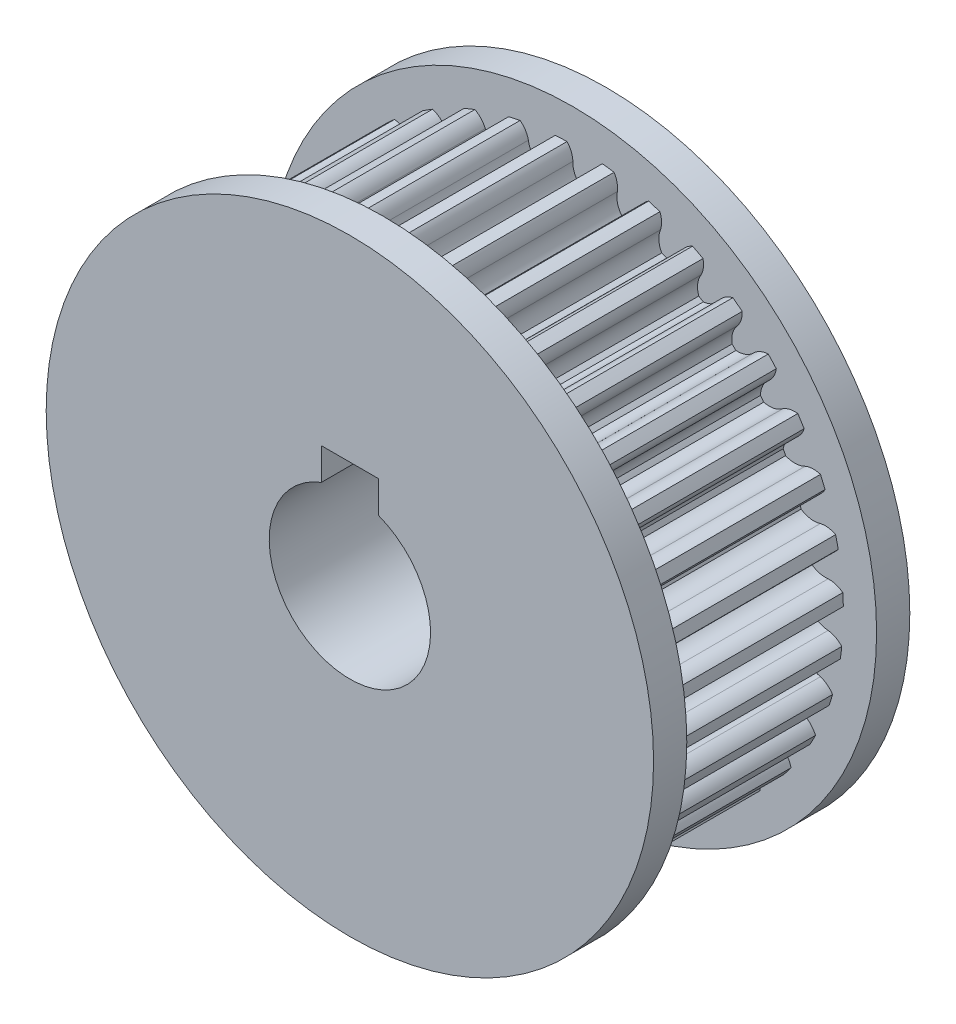
SolidWorks part; units mm, degrees
ref_plane "Alzado" through (0, 0, 0) normal (0, 0, 1) x (1, 0, 0)
ref_plane "Planta" through (0, 0, 0) normal (0, 1, 0) x (1, 0, 0)
ref_plane "Vista lateral" through (0, 0, 0) normal (1, 0, 0) x (0, 0, -1)
sketch "Croquis2" plane through (0, 0, 0) normal (0, 0, 1) x (1, 0, 0)
  circle A0 centre (0, 0) radius 25.125 construction
  arc A1 (3.1031, 28.3306) -> (-0.6204, 28.4932) centre (0, 0) ccw construction
  arc A2 (2.3548, 26.8971) -> (0, 27) centre (0, 0) ccw construction
  arc A3 (0, 27) -> (-0.6204, 28.4932) centre (-2.3548, 26.8971) ccw construction
  arc A5 (0, 27) -> (0.816, 25.1117) centre (2.3548, 26.8971) ccw construction
  circle A7 centre (0, 0) radius 28.5
  arc A8 (3.1031, 28.3306) -> (2.3548, 26.8971) centre (4.6916, 26.5893) ccw construction
  arc A10 (1.3772, 25.0872) -> (2.3548, 26.8971) centre (0, 27) ccw construction
  dimension "D1" = 50.25
  dimension "D2" = 57
  dimension "D3" = 54
  dimension "D4" = 4.714
extrude "Saliente-Extruir2" add sketch "Croquis2" along normal blind 20
sketch "Croquis5" plane through (0, 0, 20) normal (0, 0, 1) x (1, 0, 0)
  arc A0 (1.3772, 25.0872) -> (2.3548, 26.8971) centre (0, 27) ccw construction
  arc A1 (3.1031, 28.3306) -> (2.3548, 26.8971) centre (4.6916, 26.5893) ccw construction
  arc A2 (0, 27) -> (-0.6204, 28.4932) centre (-2.3548, 26.8971) ccw construction
  arc A3 (0, 27) -> (0.816, 25.1117) centre (2.3548, 26.8971) ccw construction
  circle A4 centre (0, 0) radius 25.125 construction
  arc A5 (1.3772, 25.0872) -> (2.3548, 26.8971) centre (0, 27) ccw
  arc A6 (3.1031, 28.3306) -> (2.3548, 26.8971) centre (4.6916, 26.5893) ccw
  arc A7 (0, 27) -> (-0.6204, 28.4932) centre (-2.3548, 26.8971) ccw
  arc A8 (0, 27) -> (0.816, 25.1117) centre (2.3548, 26.8971) ccw
  arc A9 (1.3772, 25.0872) -> (0.816, 25.1117) centre (0, 0) ccw
  circle A10 centre (0, 0) radius 28.5 construction
  arc A11 (3.1031, 28.3306) -> (-0.6204, 28.4932) centre (0, 0) ccw
extrude "Cortar-Extruir2" cut sketch "Croquis5" against normal blind 23
pattern_circular "MatrizC1" count 36 over 360 about axis through (0, 0, 0) along (0, 0, 1) of "Cortar-Extruir2"
sketch "Croquis6" plane through (0, 0, 20) normal (0, 0, 1) x (1, 0, 0)
  line L0 (3, 7.953) -> (3, 11.303)
  line L1 (3, 11.303) -> (-3, 11.303)
  line L2 (-3, 11.303) -> (-3, 7.953)
  line L3 (0, 0) -> (0, 11.303) construction
  arc A0 (-3, 7.953) -> (3, 7.953) centre (0, 0) ccw
  dimension "D1" = 17
  dimension "D2" = 6
  dimension "D3" = 3.35
extrude "Cortar-Extruir3" cut sketch "Croquis6" against normal blind 46
sketch "Croquis7" plane through (0, 0, 0) normal (0, 0, -1) x (-1, 0, 0)
  line L0 (-3, 7.953) -> (-3, 11.303) construction
  line L1 (-3, 11.303) -> (3, 11.303) construction
  line L2 (3, 11.303) -> (3, 7.953) construction
  line L3 (-3, 7.953) -> (-3, 11.303)
  line L4 (-3, 11.303) -> (3, 11.303)
  line L5 (3, 11.303) -> (3, 7.953)
  arc A0 (-3, 7.953) -> (3, 7.953) centre (0, 0) ccw construction
  arc A1 (-3, 7.953) -> (3, 7.953) centre (0, 0) ccw
  circle A2 centre (0, 0) radius 28.5
extrude "Saliente-Extruir3" add sketch "Croquis7" along normal blind 3.5
sketch "Croquis8" plane through (0, 0, 20) normal (0, 0, 1) x (1, 0, 0)
  line L0 (3, 7.953) -> (3, 11.303) construction
  line L1 (3, 11.303) -> (-3, 11.303) construction
  line L2 (-3, 11.303) -> (-3, 7.953) construction
  line L3 (3, 7.953) -> (3, 11.303)
  line L4 (3, 11.303) -> (-3, 11.303)
  line L5 (-3, 11.303) -> (-3, 7.953)
  circle A0 centre (0, 0) radius 28.5
  arc A1 (-3, 7.953) -> (3, 7.953) centre (0, 0) ccw construction
  arc A2 (-3, 7.953) -> (3, 7.953) centre (0, 0) ccw
extrude "Saliente-Extruir4" add sketch "Croquis8" along normal blind 3.5
sketch "Croquis9" plane through (0, 0, 23.5) normal (0, 0, 1) x (1, 0, 0)
  line L0 (-5.0991, 18.1691) -> (-18.9845, -2.2882)
sketch "Croquis10" plane through (0, 0, 20) normal (0, 0, -1) x (-1, 0, 0)
  circle A0 centre (0, 0) radius 28.5
  circle A1 centre (0, 0) radius 32
  dimension "D1" = 57
  dimension "D2" = 64
extrude "Saliente-Extruir5" add sketch "Croquis10" against normal up to surface (3.5 mm away) up to face at (28.5, 0, 23.5)
sketch "Croquis11" plane through (0, 0, 0) normal (0, 0, 1) x (1, 0, 0)
  circle A0 centre (0, 0) radius 32 construction
  circle A1 centre (0, 0) radius 32
  circle A2 centre (0, 0) radius 28.5 construction
  circle A3 centre (0, 0) radius 28.5
extrude "Saliente-Extruir6" add sketch "Croquis11" against normal up to surface (3.5 mm away) up to face at (-28.5, 0, -3.5)
